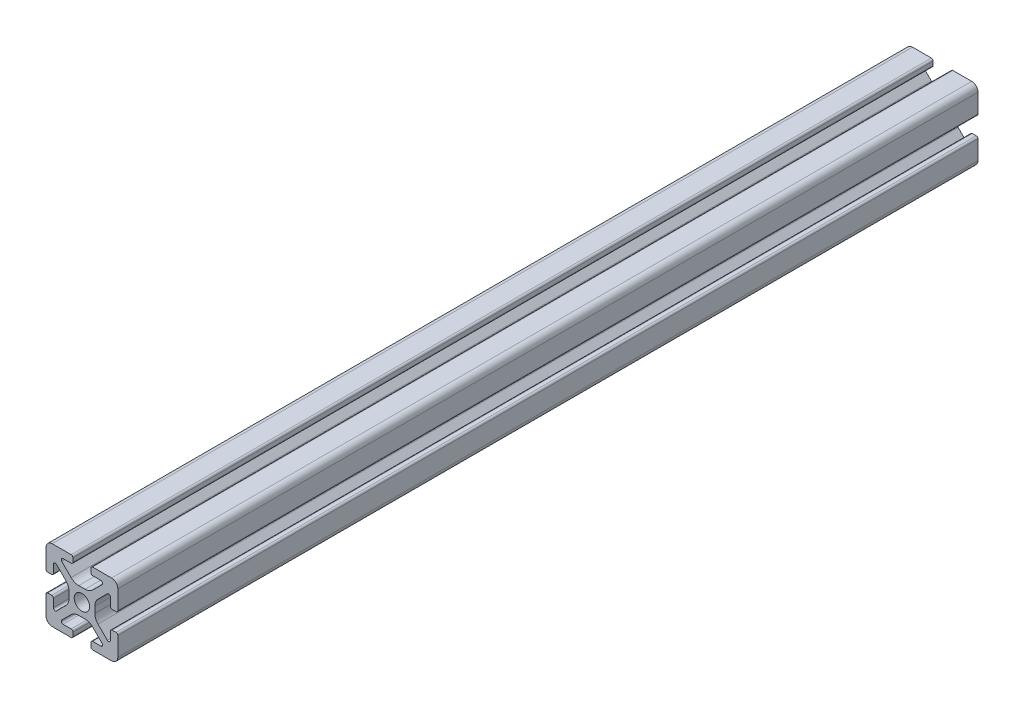
SolidWorks part; units mm, degrees
material "1060 Alloy"
ref_plane "Front Plane" through (0, 0, 0) normal (0, 0, 1) x (1, 0, 0)
ref_plane "Top Plane" through (0, 0, 0) normal (0, 1, 0) x (1, 0, 0)
ref_plane "Right Plane" through (0, 0, 0) normal (1, 0, 0) x (0, 0, -1)
sketch "Sketch2" plane through (0, 0, 0) normal (0, 0, 1) x (1, 0, 0)
  line L0 (0, 10) -> (0, -10) construction
  line L1 (-10, 0) -> (10, 0) construction
  line L2 (2.5, -10) -> (10, -10)
  line L3 (10, -10) -> (10, -2.5)
  line L4 (2.5, -10) -> (2.5, -7.9246)
  line L5 (2.5, -7.9246) -> (6.4571, -7.9246)
  line L6 (6.4571, -7.9246) -> (2.1325, -3.6)
  line L7 (0, 0) -> (10, -10) construction
  line L8 (10, -2.5) -> (7.9246, -2.5)
  line L9 (7.9246, -2.5) -> (7.9246, -6.4571)
  line L10 (7.9246, -6.4571) -> (3.6, -2.1325)
  line L11 (5.7623, -4.2948) -> (4.2948, -5.7623) construction
  circle A0 centre (0, 0) radius 2.15
  arc A1 (5.25, -7.9246) -> (5.6036, -7.0711) centre (5.25, -7.4246) ccw construction
  point P8 (0, -3.6)
  point P16 (5.0286, -5.0286)
  dimension "Center Hole Diameter" = 4.3
  dimension "D3" = 0.5
  dimension "Rail Height" = 20
  dimension "Rail Width" = 20
  dimension "T-Slot Width" = 5
  dimension "Slot Depth" = 6.4
  dimension "Slot Inner Width" = 11.5
sketch "Sketch3" plane through (0, 0, 0) normal (1, 0, 0) x (0, 0, -1)
  line L0 (-110, -10) -> (110, -10) construction
  line L1 (-84.6, 0) -> (84.6, 0) construction
  line L2 (0, 10) -> (0, -10) construction
  line L3 (0, 10) -> (0, -10) construction
  point P6 (-84.6, 0)
  point P8 (84.6, 0)
  dimension "Length" = 220
  dimension "D1" = 25.4
sketch "Sketch4" plane through (0, 0, 0) normal (0, 0, 1) x (1, 0, 0)
  line L0 (3, -10) -> (8.25, -10)
  line L1 (2.5, -10) -> (10, -10) construction
  line L2 (2.5, -10) -> (2.5, -7.9246) construction
  line L3 (2.5, -7.9246) -> (6.4571, -7.9246) construction
  line L4 (2.5, -8.4246) -> (2.5, -9.5)
  line L5 (3, -7.9246) -> (5.25, -7.9246)
  line L6 (0, -3.6) -> (0.8898, -3.6)
  line L7 (6.4571, -7.9246) -> (2.1325, -3.6) construction
  line L8 (3.0112, -4.4787) -> (5.6036, -7.0711)
  line L9 (10, -10) -> (10, -2.5) construction
  line L10 (7.9246, -6.4571) -> (3.6, -2.1325) construction
  line L11 (7.9246, -2.5) -> (7.9246, -6.4571) construction
  line L12 (7.9246, -5.25) -> (7.9246, -3)
  line L13 (10, -2.5) -> (7.9246, -2.5) construction
  line L14 (8.4246, -2.5) -> (9.5, -2.5)
  line L15 (10, -3) -> (10, -8.25)
  line L16 (7.0711, -5.6036) -> (4.4787, -3.0112)
  line L17 (3.6, 0) -> (3.6, -0.8898)
  line L18 (-10, 0) -> (10, 0) construction
  line L19 (0, -3.6) -> (0, -2.15)
  line L20 (0, 10) -> (0, -10) construction
  line L21 (3.6, 0) -> (2.15, 0)
  arc A0 (2.5, -9.5) -> (3, -10) centre (3, -9.5) ccw
  arc A1 (5.25, -7.9246) -> (5.6036, -7.0711) centre (5.25, -7.4246) ccw construction
  arc A2 (2.5, -8.4246) -> (3, -7.9246) centre (3, -8.4246) cw
  arc A3 (5.25, -7.9246) -> (5.6036, -7.0711) centre (5.25, -7.4246) ccw
  arc A4 (0.8898, -3.6) -> (3.0112, -4.4787) centre (0.8898, -6.6) cw
  arc A5 (8.25, -10) -> (10, -8.25) centre (8.25, -8.25) ccw
  arc A6 (7.0711, -5.6036) -> (7.9246, -5.25) centre (7.4246, -5.25) ccw
  arc A7 (7.9246, -3) -> (8.4246, -2.5) centre (8.4246, -3) cw
  arc A8 (9.5, -2.5) -> (10, -3) centre (9.5, -3) cw
  arc A9 (4.4787, -3.0112) -> (3.6, -0.8898) centre (6.6, -0.8898) cw
  circle A10 centre (0, 0) radius 2.15 construction
  arc A11 (0, -2.15) -> (2.15, 0) centre (0, 0) ccw
  dimension "D1" = 1.75
  dimension "D2" = 3
extrude "Boss-Extrude1" add sketch "Sketch4" along normal mid plane 242
mirror "Mirror1" about plane through (0, 0, 0) normal (1, 0, 0) of bodies 134
mirror "Mirror2" about plane through (0, 0, 0) normal (0, 1, 0) of bodies 135
sketch "Sketch5" plane through (0, 0, 121) normal (0, 0, 1) x (1, 0, 0)
  line L1 (-13.9539, 12.3566) -> (13.8334, 12.3566)
  line L2 (-13.9539, 12.3566) -> (-13.9539, -13.6827)
  line L3 (-13.9539, -13.6827) -> (13.8334, -13.6827)
  line L4 (13.8334, 12.3566) -> (13.8334, -13.6827)
extrude "Cut-Extrude1" cut sketch "Sketch5" against normal blind 2.4
equation "\"D3@Sketch2\"=\"T-Slot Width@Sketch2\"*0.1"
equation "\"D1@Sketch4\"=\"D3@Sketch2\"*3.5"
equation "\"D2@Sketch4\"=\"D3@Sketch2\"*6"
equation "\"D1@Boss-Extrude1\"= \"Length@Sketch3\" * 12.1 / 11"
